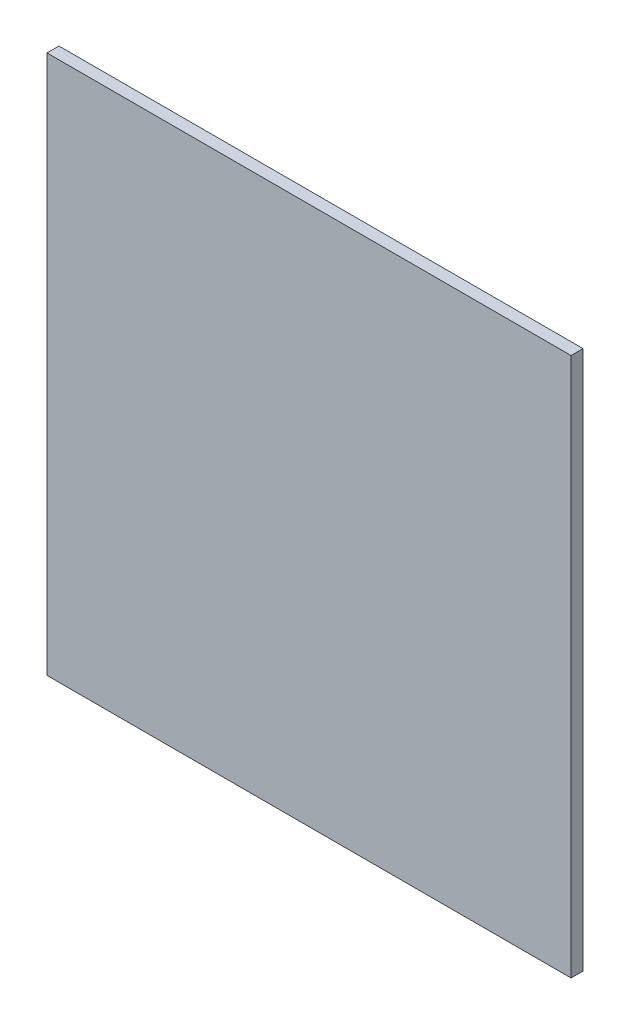
SolidWorks part; units mm, degrees
ref_plane "前视基准面" through (0, 0, 0) normal (0, 0, 1) x (1, 0, 0)
ref_plane "上视基准面" through (0, 0, 0) normal (0, 1, 0) x (1, 0, 0)
ref_plane "右视基准面" through (0, 0, 0) normal (1, 0, 0) x (0, 0, -1)
sketch "草图1" plane through (0, 0, 0) normal (0, 0, 1) x (1, 0, 0)
  line L1 (-87.5, 90) -> (87.5, 90)
  line L2 (-87.5, 90) -> (-87.5, -90)
  line L3 (-87.5, -90) -> (87.5, -90)
  line L4 (87.5, 90) -> (87.5, -90)
  line L5 (-87.5, 90) -> (87.5, -90) construction
  line L6 (-87.5, -90) -> (87.5, 90) construction
  point P0 (0, 0)
  dimension "D1" = 175
  dimension "D2" = 180
extrude "凸台-拉伸1" add sketch "草图1" along normal blind 4
